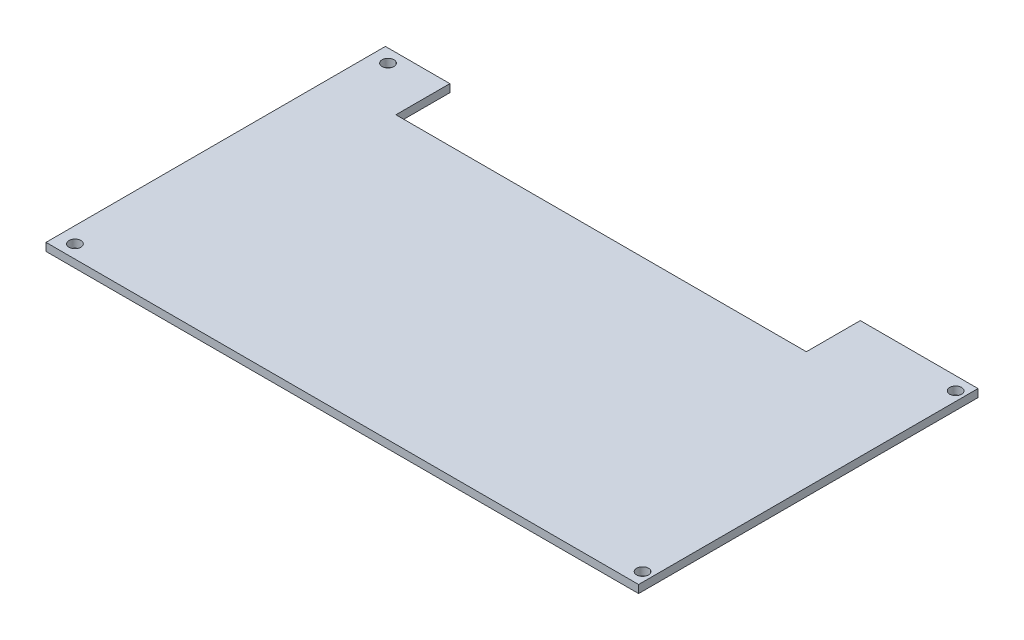
SolidWorks part; units mm, degrees
ref_plane "Front Plane" through (0, 0, 0) normal (0, 0, 1) x (1, 0, 0)
ref_plane "Top Plane" through (0, 0, 0) normal (0, 1, 0) x (1, 0, 0)
ref_plane "Right Plane" through (0, 0, 0) normal (1, 0, 0) x (0, 0, -1)
sketch "Sketch1" plane through (0, 0, 0) normal (0, 1, 0) x (1, 0, 0)
  line L0 (-112.62, 129) -> (-112.62, 0)
  line L1 (-112.62, 0) -> (112.62, 0)
  line L2 (112.62, 0) -> (112.62, 129)
  line L3 (112.62, 129) -> (67.88, 129)
  line L4 (67.88, 129) -> (67.88, 108.5)
  line L5 (67.88, 108.5) -> (-88.12, 108.5)
  line L6 (-88.12, 108.5) -> (-88.12, 129)
  line L7 (-88.12, 129) -> (-112.62, 129)
  dimension "D1" = 129
  dimension "D2" = 225.24
  dimension "D3" = 24.5
  dimension "D4" = 44.74
  dimension "D5" = 20.5
extrude "Boss-Extrude1" add sketch "Sketch1" along normal blind 3
hole_wizard "M4 Clearance Hole1" positions "Sketch2" profile "Sketch3" hole size "M4" standard "ANSI Metric"
sketch "Sketch2" plane through (0, 3, 0) normal (0, 1, 0) x (1, 0, 0)
  point P0 (-106.62, 5)
  point P2 (-106.62, 124)
  point P4 (109.12, 124)
  point P6 (109.12, 5)
sketch "Sketch3" plane through (-106.62, 3, -5) normal (1, 0, 0) x (0, 0, 1)
  line L0 (0, 0) -> (0, 13.3519)
  line L1 (0, 13.3519) -> (2.25, 12)
  line L2 (2.25, 12) -> (2.25, 0)
  line L5 (2.25, 0) -> (0, 0)
  line L10 (0, 13.3519) -> (-2.25, 12) construction
  line L11 (0, -6.35) -> (0, 107.95) construction
  dimension "Hole Dia." = 4.5
  dimension "Hole Depth" = 12
  dimension "Drill Angle" = 118
